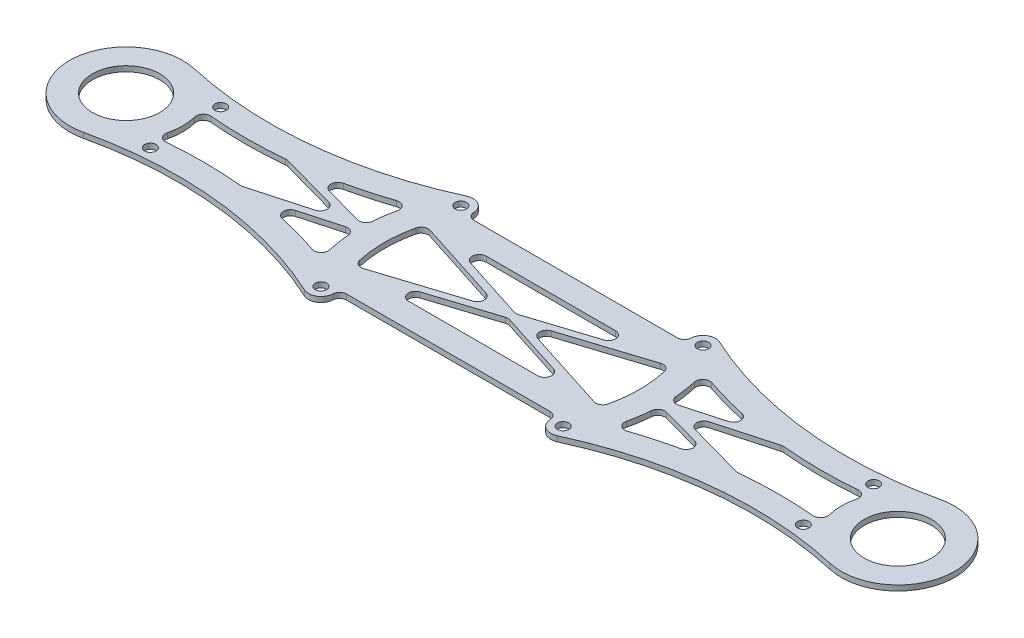
SolidWorks part; units mm, degrees
material "1023 Carbon Steel Sheet (SS)"
ref_plane "Front Plane" through (0, 0, 0) normal (0, 0, 1) x (1, 0, 0)
ref_plane "Top Plane" through (0, 0, 0) normal (0, 1, 0) x (1, 0, 0)
ref_plane "Right Plane" through (0, 0, 0) normal (1, 0, 0) x (0, 0, -1)
sketch "Sketch1" plane through (0, 0, 0) normal (0, 1, 0) x (1, 0, 0)
  line L0 (0, 43) -> (0, -43) construction
  line L1 (0, 0) -> (-43, 0) construction
  line L2 (0, 0) -> (-37.2391, 21.5) construction
  line L3 (0, 0) -> (-37.2391, -21.5) construction
  line L4 (-31.1769, 18) -> (31.1769, 18)
  line L5 (31.1769, -18) -> (-31.1769, -18)
  arc A0 (-37.2391, 21.5) -> (-37.2391, -21.5) centre (0, 0) ccw
  arc A1 (-31.1769, 18) -> (-31.1769, -18) centre (0, 0) ccw
  arc A2 (-105.4595, 15.6034) -> (-105.4595, -15.6034) centre (-109, 0) ccw
  circle A3 centre (-34.208, 19.75) radius 3.5
  circle A4 centre (-34.208, -19.75) radius 3.5
  arc A5 (-105.4595, 15.6034) -> (-35.6743, 22.928) centre (-81.3396, 121.9012) ccw
  arc A6 (-105.4595, -15.6034) -> (-35.6743, -22.928) centre (-81.3396, -121.9012) cw
  arc A7 (105.4595, -15.6034) -> (35.6743, -22.928) centre (81.3396, -121.9012) ccw
  arc A8 (105.4595, 15.6034) -> (35.6743, 22.928) centre (81.3396, 121.9012) cw
  circle A9 centre (34.208, -19.75) radius 3.5
  circle A10 centre (34.208, 19.75) radius 3.5
  arc A11 (105.4595, 15.6034) -> (105.4595, -15.6034) centre (109, 0) cw
  arc A12 (31.1769, 18) -> (31.1769, -18) centre (0, 0) cw
  arc A13 (37.2391, 21.5) -> (37.2391, -21.5) centre (0, 0) cw
  dimension "D1" = 86
  dimension "D2" = 7
  dimension "D3" = 32
  dimension "D4" = 109
  dimension "D5" = 0
  dimension "D8" = 109
  dimension "D6" = 30
  dimension "D7" = 30
  dimension "D9" = 36
extrude "Boss-Extrude1" add sketch "Sketch1" along normal mid plane 1.5 contours A2 A6 A4 A0 A3 A5 | A4 A1 A3 A0 | A4 | A3 | A12 L4 A1 L5 | A10 | A13 A10 A12 A9 | A9 | A10 A13 A9 A7 A11 A8
hole_wizard "Ø3.2 (3.2) Diameter Hole1" positions "Sketch3" profile "Sketch2" hole size "Ø3.2" standard "ANSI Metric" end condition through all
sketch "Sketch3" plane through (0, 0.75, 0) normal (0, 1, 0) x (1, 0, 0)
  circle A0 centre (-109, 0) radius 16
  circle A1 centre (109, 0) radius 16
  circle A2 centre (-92.2167, 9.9283) radius 3.5
  circle A3 centre (-92.2167, -9.9283) radius 3.5
  arc A4 (-105.4595, 15.6034) -> (-35.6743, 22.928) centre (-81.3396, 121.9012) ccw construction
  arc A5 (-35.6743, -22.928) -> (-105.4595, -15.6034) centre (-81.3396, -121.9012) ccw construction
  circle A6 centre (92.2167, 9.9283) radius 3.5
  circle A7 centre (92.2167, -9.9283) radius 3.5
  arc A8 (105.4595, -15.6034) -> (35.6743, -22.928) centre (81.3396, -121.9012) ccw construction
  arc A9 (35.6743, 22.928) -> (105.4595, 15.6034) centre (81.3396, 121.9012) ccw construction
  point P0 (-34.208, 19.75)
  point P3 (-34.208, -19.75)
  point P6 (34.208, -19.75)
  point P9 (34.208, 19.75)
  point P20 (-92.2167, 9.9283)
  point P22 (-92.2167, -9.9283)
  point P36 (92.2167, 9.9283)
  point P38 (92.2167, -9.9283)
  dimension "D1" = 7
sketch "Sketch2" plane through (-34.208, 0.75, -19.75) normal (1, 0, 0) x (0, 0, 1)
  line L0 (0, 0) -> (0, 1.5)
  line L1 (0, 1.5) -> (1.6, 1.5)
  line L2 (1.6, 1.5) -> (1.6, 0)
  line L5 (1.6, 0) -> (0, 0)
  line L11 (0, -6.35) -> (0, 107.95) construction
  dimension "Thru Hole Dia." = 3.2
  dimension "Thru Hole Depth" = 1.5
sketch "Sketch4" plane through (0, 0.75, 0) normal (0, 1, 0) x (1, 0, 0)
  line L0 (0, 18) -> (0, -18) construction
  line L1 (-31.1769, 18) -> (31.1769, 18) construction
  line L2 (31.1769, -18) -> (-31.1769, -18) construction
  line L3 (-43, 0) -> (-67.3057, -6.7532)
  line L4 (-43, 0) -> (-67.3057, 6.7532)
  line L7 (-42.7323, 0.9635) -> (-67.038, 7.7167)
  line L8 (-42.7323, -0.9635) -> (-67.038, -7.7167)
  line L9 (-43.2677, 0.9635) -> (-69.9809, -6.4586)
  line L10 (-43.2677, -0.9635) -> (-69.9809, 6.4586)
  line L11 (-43.2677, -0.9635) -> (-67.5734, 5.7897) construction
  line L12 (-43.2677, 0.9635) -> (-67.5734, -5.7897) construction
  line L13 (43.2677, -0.9635) -> (69.9809, 6.4586)
  line L14 (43.2677, 0.9635) -> (69.9809, -6.4586)
  line L15 (42.7323, -0.9635) -> (67.038, -7.7167)
  line L16 (42.7323, 0.9635) -> (67.038, 7.7167)
  line L17 (43, 0) -> (67.3057, 6.7532)
  line L18 (43, 0) -> (67.3057, -6.7532)
  circle A0 centre (-109, 0) radius 9.5
  arc A1 (-40.935, 13.1654) -> (-40.935, -13.1654) centre (0, 0) ccw
  arc A4 (-107.0084, 8.7769) -> (-32.7417, 16.572) centre (-81.3396, 121.9012) ccw
  arc A5 (-94.4446, 6.6438) -> (-40.935, 13.1654) centre (-81.3396, 121.9012) ccw
  arc A6 (-94.4446, -6.6438) -> (-94.4446, 6.6438) centre (-109, 0) ccw
  arc A7 (-32.7417, -16.572) -> (-107.0084, -8.7769) centre (-81.3396, -121.9012) ccw
  arc A8 (-40.935, -13.1654) -> (-94.4446, -6.6438) centre (-81.3396, -121.9012) ccw
  arc A19 (40.935, -13.1654) -> (94.4446, -6.6438) centre (81.3396, -121.9012) cw
  arc A20 (94.4446, -6.6438) -> (94.4446, 6.6438) centre (109, 0) cw
  arc A21 (94.4446, 6.6438) -> (40.935, 13.1654) centre (81.3396, 121.9012) cw
  arc A22 (40.935, 13.1654) -> (40.935, -13.1654) centre (0, 0) cw
  circle A23 centre (109, 0) radius 9.5
  dimension "D1" = 19
  dimension "D2" = 86
  dimension "D3" = 7
  dimension "D4" = 7
  dimension "D5" = 1
  dimension "D6" = 1
  dimension "D7" = 1
  dimension "D8" = 1
extrude "Cut-Extrude1" cut sketch "Sketch4" against normal through all contours A0 | A8 L9 L10 A5 A6 | A5 L7 A1 | A8 A1 L8 | A20 A21 L13 L14 A19 | A21 A22 L16 | L15 A22 A19 | A23
sketch "Sketch5" plane through (0, 0.75, 0) normal (0, 1, 0) x (1, 0, 0)
  line L2 (-31.1769, 11) -> (31.1769, 11)
  line L3 (-34.2783, 11) -> (34.2783, 11)
  line L4 (-34.2783, -11) -> (34.2783, 11)
  line L5 (31.1769, -11) -> (-31.1769, -11)
  line L6 (34.2783, -11) -> (-34.2783, -11)
  line L7 (34.2783, -11) -> (-34.2783, 11)
  line L8 (34.5838, -10.0478) -> (-33.9727, 11.9522)
  line L9 (33.9727, -11.9522) -> (-34.5838, 10.0478)
  line L10 (-34.5838, -10.0478) -> (33.9727, 11.9522)
  line L11 (-33.9727, -11.9522) -> (34.5838, 10.0478)
  arc A0 (-33.9595, 11.9479) -> (-33.9595, -11.9479) centre (0, 0) ccw
  arc A1 (33.9595, -11.9479) -> (33.9595, 11.9479) centre (0, 0) ccw
  dimension "D1" = 7
  dimension "D2" = 7
  dimension "D3" = 1
  dimension "D4" = 1
  dimension "D5" = 1
  dimension "D6" = 1
extrude "Cut-Extrude4" cut sketch "Sketch5" against normal through all contours L9 A0 L10 | L8 A1 L11 | L8 L10 L3 | L11 L6 L9
fillet "Fillet1" radius 2 38 edges at (46.7355, 0, 0) (-31.1769, 0, 18) (-31.1769, 0, -18) (31.1769, 0, -18) (31.1769, 0, 18) (40.935, 0, -13.1654) (42.9876, 0, -1.0344) (42.9876, 0, 1.0344) (40.935, 0, 13.1654) (64.7797, 0, 7.0893) (69.9809, 0, 6.4586) (69.9809, 0, -6.4586) (94.4446, 0, -6.6438) (94.4446, 0, 6.6438) (64.7797, 0, -7.0893) (31.0055, 0, 11) (34.5706, 0, 10.0436) (31.0055, 0, -11) (34.5706, 0, -10.0436) (0, 0, 1.0502) (-3.2727, 0, 0) (3.2727, 0, 0) (-31.0055, 0, -11) (-34.5706, 0, -10.0436) (-31.0055, 0, 11) (0, 0, -1.0502) (-34.5706, 0, 10.0436) (-64.7797, 0, 7.0893) (-64.7797, 0, -7.0893) (-40.935, 0, -13.1654) (-42.9876, 0, 1.0344) (-46.7355, 0, 0) (-40.935, 0, 13.1654) (-42.9876, 0, -1.0344) (-69.9809, 0, 6.4586) (-69.9809, 0, -6.4586) (-94.4446, 0, -6.6438) (-94.4446, 0, 6.6438)
